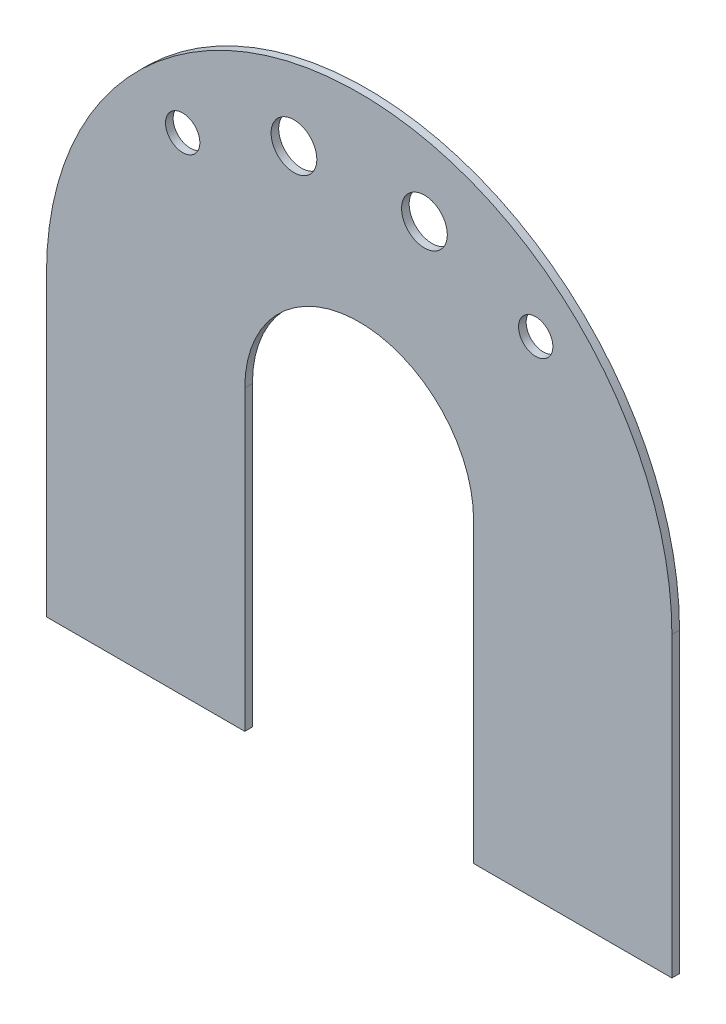
SolidWorks part; units mm, degrees
material "Q235"
ref_plane "前视基准面" through (0, 0, 0) normal (0, 0, 1) x (1, 0, 0)
ref_plane "上视基准面" through (0, 0, 0) normal (0, 1, 0) x (1, 0, 0)
ref_plane "右视基准面" through (0, 0, 0) normal (1, 0, 0) x (0, 0, -1)
sketch "草图1" plane through (0, 0, 0) normal (0, 0, 1) x (1, 0, 0)
  line L1 (-410, 0) -> (-410, -390)
  line L2 (-410, -390) -> (410, -390)
  line L3 (410, -390) -> (410, 0)
  arc A0 (410, 0) -> (-410, 0) centre (0, 0) ccw
  dimension "D1" = 820
  dimension "D2" = 390
extrude "凸台-拉伸1" add sketch "草图1" along normal blind 10
sketch "草图3" plane through (0, 0, 10) normal (0, 0, 1) x (1, 0, 0)
  line L0 (0, 410) -> (0, 0) construction
  line L1 (-150, 0) -> (-150, -390)
  line L2 (-150, -390) -> (150, -390)
  line L3 (150, -390) -> (150, 0)
  line L4 (-410, -390) -> (410, -390) construction
  circle A0 centre (-85.5363, 306.6659) radius 30
  circle A1 centre (85.5363, 306.6659) radius 30
  circle A2 centre (-231.4154, 248.9733) radius 22.5
  circle A3 centre (231.4154, 248.9733) radius 22.5
  arc A4 (410, 0) -> (-410, 0) centre (0, 0) ccw construction
  arc A5 (150, 0) -> (-150, 0) centre (0, 0) ccw
  dimension "D1" = 0
  dimension "D2" = 60
  dimension "D4" = 60
  dimension "D5" = 45
  dimension "D7" = 45
  dimension "D3" = 300
extrude "切除-拉伸3" cut sketch "草图3" against normal blind 50
